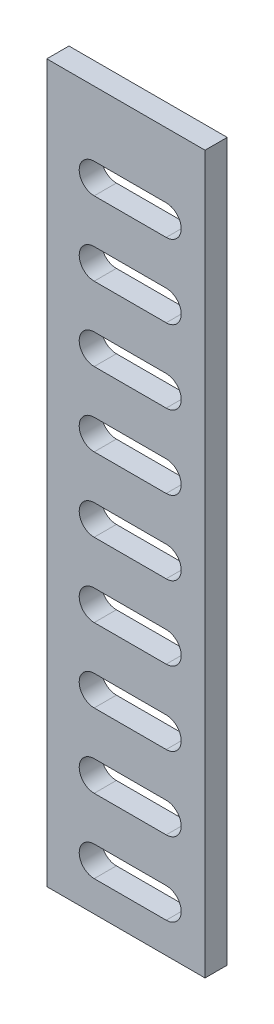
SolidWorks part; units mm, degrees
ref_plane "Front Plane" through (0, 0, 0) normal (0, 0, 1) x (1, 0, 0)
ref_plane "Top Plane" through (0, 0, 0) normal (0, 1, 0) x (1, 0, 0)
ref_plane "Right Plane" through (0, 0, 0) normal (1, 0, 0) x (0, 0, -1)
sketch "Sketch1" plane through (0, 0, 0) normal (0, 0, 1) x (1, 0, 0)
  line L6 (-80.9402, 33.9086) -> (-102.3514, 33.9086)
  line L7 (-80.9402, 130.9021) -> (-102.3514, 130.9021)
  line L8 (-91.0668, 24.5794) -> (-91.0668, 142.0861) construction
  line L9 (-86.196, 40.0812) -> (-95.9377, 40.0812) construction
  line L10 (-102.3514, 130.9021) -> (-102.3514, 33.9086)
  line L11 (-80.9402, 130.9021) -> (-80.9402, 33.9086)
  line L12 (-86.196, 38.0536) -> (-95.9377, 38.0536)
  line L13 (-86.196, 42.1089) -> (-95.9377, 42.1089)
  line L14 (-86.196, 50.0812) -> (-95.9377, 50.0812) construction
  line L15 (-86.196, 48.0536) -> (-95.9377, 48.0536)
  line L16 (-86.196, 52.1089) -> (-95.9377, 52.1089)
  line L17 (-86.196, 60.0812) -> (-95.9377, 60.0812) construction
  line L20 (-86.196, 58.0536) -> (-95.9377, 58.0536)
  line L23 (-86.196, 62.1089) -> (-95.9377, 62.1089)
  line L26 (-86.196, 70.0812) -> (-95.9377, 70.0812) construction
  line L29 (-86.196, 68.0536) -> (-95.9377, 68.0536)
  line L32 (-86.196, 72.1089) -> (-95.9377, 72.1089)
  line L35 (-86.196, 80.0812) -> (-95.9377, 80.0812) construction
  line L38 (-86.196, 78.0536) -> (-95.9377, 78.0536)
  line L39 (-86.196, 82.1089) -> (-95.9377, 82.1089)
  line L40 (-86.196, 90.0812) -> (-95.9377, 90.0812) construction
  line L41 (-86.196, 88.0536) -> (-95.9377, 88.0536)
  line L42 (-86.196, 92.1089) -> (-95.9377, 92.1089)
  line L43 (-86.196, 100.0812) -> (-95.9377, 100.0812) construction
  line L44 (-86.196, 98.0536) -> (-95.9377, 98.0536)
  line L45 (-86.196, 102.1089) -> (-95.9377, 102.1089)
  line L46 (-86.196, 110.0812) -> (-95.9377, 110.0812) construction
  line L47 (-86.196, 108.0536) -> (-95.9377, 108.0536)
  line L48 (-86.196, 112.1089) -> (-95.9377, 112.1089)
  line L49 (-86.196, 120.0812) -> (-95.9377, 120.0812) construction
  line L50 (-86.196, 118.0536) -> (-95.9377, 118.0536)
  line L51 (-86.196, 122.1089) -> (-95.9377, 122.1089)
  arc A0 (-86.196, 38.0536) -> (-86.196, 42.1089) centre (-86.196, 40.0812) ccw
  arc A1 (-95.9377, 42.1089) -> (-95.9377, 38.0536) centre (-95.9377, 40.0812) ccw
  arc A2 (-86.196, 48.0536) -> (-86.196, 52.1089) centre (-86.196, 50.0812) ccw
  arc A3 (-95.9377, 52.1089) -> (-95.9377, 48.0536) centre (-95.9377, 50.0812) ccw
  arc A18 (-86.196, 58.0536) -> (-86.196, 62.1089) centre (-86.196, 60.0812) ccw
  arc A19 (-95.9377, 62.1089) -> (-95.9377, 58.0536) centre (-95.9377, 60.0812) ccw
  arc A20 (-86.196, 68.0536) -> (-86.196, 72.1089) centre (-86.196, 70.0812) ccw
  arc A21 (-95.9377, 72.1089) -> (-95.9377, 68.0536) centre (-95.9377, 70.0812) ccw
  arc A22 (-86.196, 78.0536) -> (-86.196, 82.1089) centre (-86.196, 80.0812) ccw
  arc A23 (-95.9377, 82.1089) -> (-95.9377, 78.0536) centre (-95.9377, 80.0812) ccw
  arc A24 (-86.196, 88.0536) -> (-86.196, 92.1089) centre (-86.196, 90.0812) ccw
  arc A25 (-95.9377, 92.1089) -> (-95.9377, 88.0536) centre (-95.9377, 90.0812) ccw
  arc A26 (-86.196, 98.0536) -> (-86.196, 102.1089) centre (-86.196, 100.0812) ccw
  arc A27 (-95.9377, 102.1089) -> (-95.9377, 98.0536) centre (-95.9377, 100.0812) ccw
  arc A28 (-86.196, 108.0536) -> (-86.196, 112.1089) centre (-86.196, 110.0812) ccw
  arc A29 (-95.9377, 112.1089) -> (-95.9377, 108.0536) centre (-95.9377, 110.0812) ccw
  arc A30 (-86.196, 118.0536) -> (-86.196, 122.1089) centre (-86.196, 120.0812) ccw
  arc A31 (-95.9377, 122.1089) -> (-95.9377, 118.0536) centre (-95.9377, 120.0812) ccw
  point P8 (-91.0668, 40.0812)
  point P15 (-91.0668, 50.0812)
  point P23 (-91.0668, 60.0812)
  point P30 (-91.0668, 70.0812)
  point P37 (-91.0668, 80.0812)
  point P44 (-91.0668, 90.0812)
  point P51 (-91.0668, 100.0812)
  point P58 (-91.0668, 110.0812)
  point P65 (-91.0668, 120.0812)
  dimension "D1" = 10
  dimension "D2" = 8
extrude "Boss-Extrude1" add sketch "Sketch1" along normal blind 3
